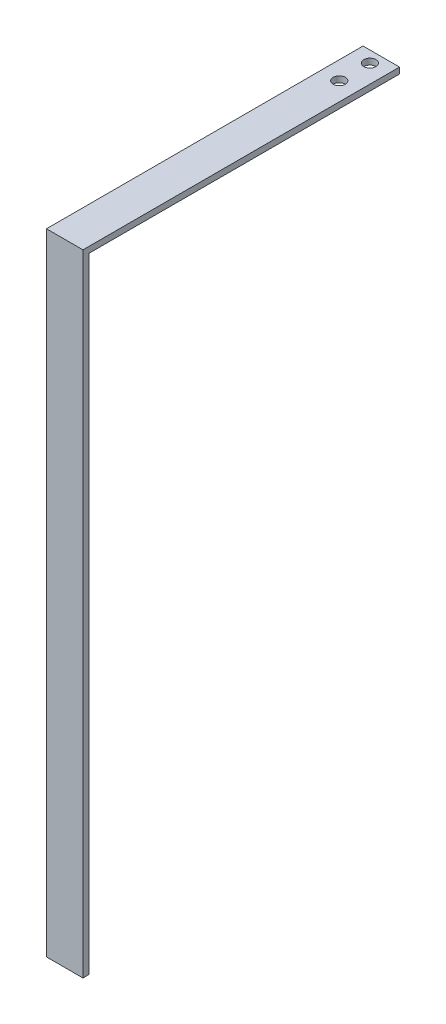
SolidWorks part; units mm, degrees
ref_plane "Alzado" through (0, 0, 0) normal (0, 0, 1) x (1, 0, 0)
ref_plane "Planta" through (0, 0, 0) normal (0, 1, 0) x (1, 0, 0)
ref_plane "Vista lateral" through (0, 0, 0) normal (1, 0, 0) x (0, 0, -1)
sketch "Croquis1" plane through (0, 0, 0) normal (0, 0, 1) x (1, 0, 0)
  line L1 (-19.05, 3.155) -> (19.05, 3.155)
  line L2 (-19.05, 3.155) -> (-19.05, -3.155)
  line L3 (-19.05, -3.155) -> (19.05, -3.155)
  line L4 (19.05, 3.155) -> (19.05, -3.155)
  line L5 (-19.05, 3.155) -> (19.05, -3.155) construction
  line L6 (-19.05, -3.155) -> (19.05, 3.155) construction
  point P0 (0, 0)
  dimension "D1" = 38.1
  dimension "D2" = 6.31
extrude "Saliente-Extruir1" add sketch "Croquis1" along normal blind 330.7
sketch "Croquis3" plane through (0, -3.155, 0) normal (0, -1, 0) x (1, 0, 0)
  line L1 (19.05, 324.39) -> (-19.05, 324.39)
  line L2 (19.05, 324.39) -> (19.05, 330.7)
  line L3 (19.05, 330.7) -> (-19.05, 330.7)
  line L4 (-19.05, 324.39) -> (-19.05, 330.7)
  line L5 (19.05, 324.39) -> (-19.05, 330.7) construction
  line L6 (19.05, 330.7) -> (-19.05, 324.39) construction
  point P0 (0, 327.545)
  dimension "D1" = 6.31
extrude "Saliente-Extruir2" add sketch "Croquis3" along normal blind 652.48
sketch "Croquis4" plane through (0, 0, 330.7) normal (0, 0, 1) x (1, 0, 0)
  line L0 (-19.05, -655.635) -> (19.05, -655.635)
  line L1 (19.05, -655.635) -> (19.05, -661.945)
  line L2 (19.05, -661.945) -> (-19.05, -661.945)
  line L3 (-19.05, -661.945) -> (-19.05, -655.635)
  dimension "D1" = 6.31
sketch "Croquis5" plane through (0, 3.155, 0) normal (0, 1, 0) x (1, 0, 0)
  circle A0 centre (0, -43.8922) radius 6.35
  circle A1 centre (0, -11.8922) radius 6.35
extrude "Cortar-Extruir1" cut sketch "Croquis5" against normal blind 6.31
